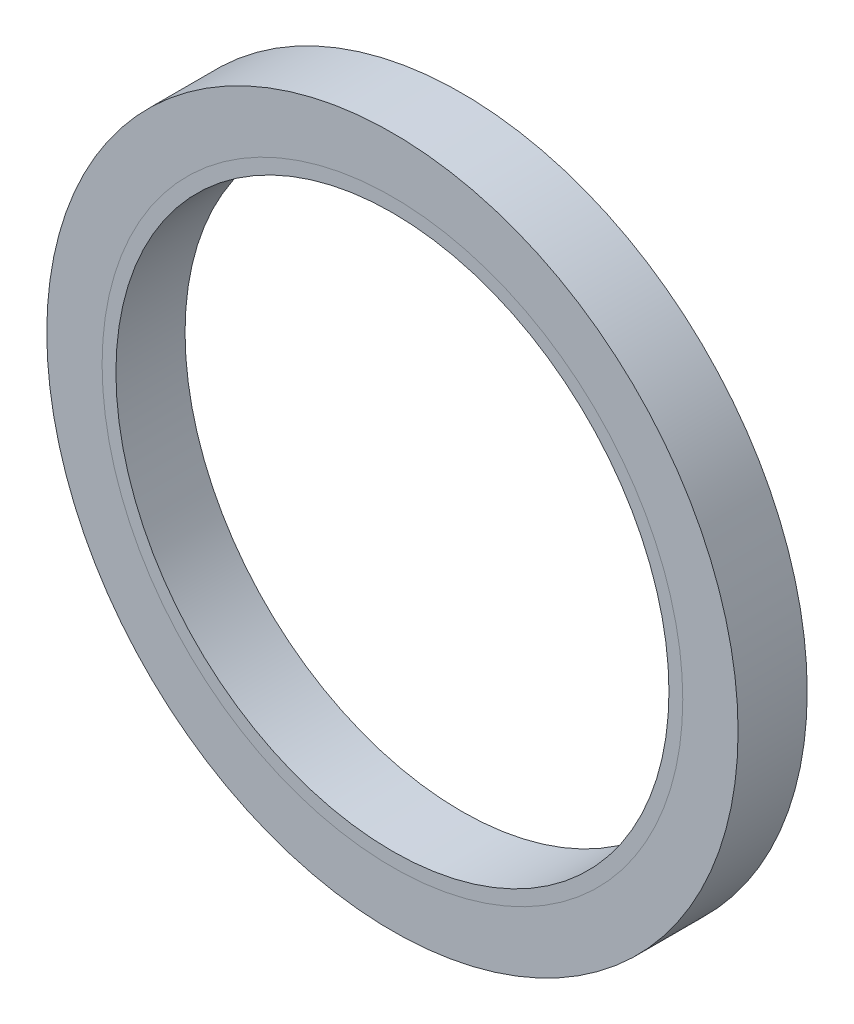
SolidWorks part; units mm, degrees
ref_plane "前视基准面" through (0, 0, 0) normal (0, 0, 1) x (1, 0, 0)
ref_plane "上视基准面" through (0, 0, 0) normal (0, 1, 0) x (1, 0, 0)
ref_plane "右视基准面" through (0, 0, 0) normal (1, 0, 0) x (0, 0, -1)
sketch "草图1" plane through (0, 0, 0) normal (0, 0, 1) x (1, 0, 0)
  circle A0 centre (0, 0) radius 40
  circle A1 centre (0, 0) radius 50
  dimension "D1" = 40
  dimension "D2" = 50
extrude "凸台-拉伸1" add sketch "草图1" along normal blind 10
sketch "草图2" plane through (0, 0, 10) normal (0, 0, 1) x (1, 0, 0)
  circle A0 centre (0, 0) radius 42
  dimension "D1" = 42
split line "分割线1"
